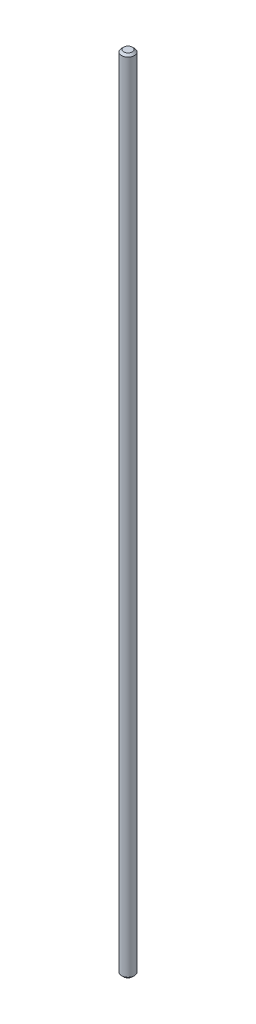
SolidWorks part; units mm, degrees
ref_plane "前基準面" through (0, 0, 0) normal (0, 0, 1) x (1, 0, 0)
ref_plane "上基準面" through (0, 0, 0) normal (0, 1, 0) x (1, 0, 0)
ref_plane "右基準面" through (0, 0, 0) normal (1, 0, 0) x (0, 0, -1)
sketch "草圖1" plane through (0, 0, 0) normal (0, 1, 0) x (1, 0, 0)
  circle A0 centre (0, 0) radius 3000
  dimension "D1" = 6000
extrude "填料-伸長1" add sketch "草圖1" along normal blind 375000
chamfer "導角1" distance 1000 angle 45 2 edges at (0, 375000, 3000) (0, 0, 3000)
